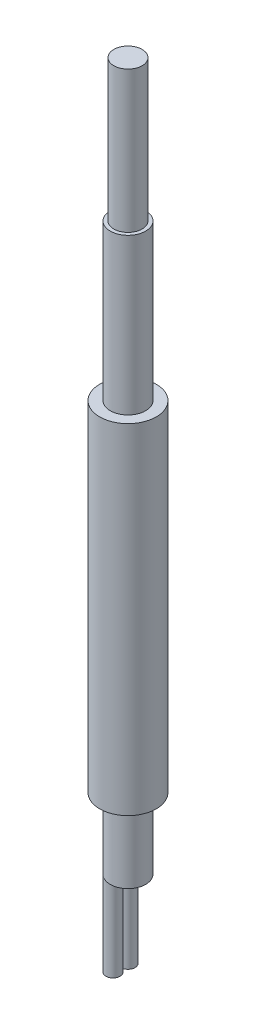
SolidWorks part; units mm, degrees
ref_plane "Ebene vorne" through (0, 0, 0) normal (0, 0, 1) x (1, 0, 0)
ref_plane "Ebene oben" through (0, 0, 0) normal (0, 1, 0) x (1, 0, 0)
ref_plane "Ebene rechts" through (0, 0, 0) normal (1, 0, 0) x (0, 0, -1)
sketch "Skizze1" plane through (0, 0, 0) normal (0, 1, 0) x (1, 0, 0)
  circle A0 centre (0, 0) radius 0.625
  circle A1 centre (0, 0) radius 0.5
  dimension "D1" = 1.25
  dimension "D2" = 0.125
extrude "Aufsatz-Linear austragen1" add sketch "Skizze1" along normal blind 20
sketch "Skizze2" plane through (0, 20, 0) normal (0, 1, 0) x (1, 0, 0)
  circle A0 centre (0, 0) radius 0.5
  dimension "D1" = 1
extrude "Aufsatz-Linear austragen2" add sketch "Skizze2" along normal blind 5 and the other way up to surface (20 mm away) separate body other way up to face at (0, 0, 0.625)
ref_plane "Ebene1" through (0, 2.5, 0) normal (0, 1, 0) x (1, 0, 0)
sketch "Skizze3" plane through (0, 2.5, 0) normal (0, 1, 0) x (1, 0, 0)
  circle A0 centre (0, 0) radius 1
  dimension "D1" = 2
extrude "Linear-Austragen-Dünn1" add sketch "Skizze3" along normal blind 12 separate body thin thin type one direction reverse wall 0.375
sketch "Skizze5" plane through (0, 0, 0) normal (0, -1, 0) x (1, 0, 0)
  line L0 (0, 0) -> (-0.625, 0) construction
  line L1 (0, 0) -> (0, -0.625) construction
  line L2 (0, 0) -> (-0.2652, -0.2652) construction
  circle A0 centre (0, 0) radius 0.625 construction
  circle A1 centre (-0.2652, -0.2652) radius 0.25
  circle A2 centre (0, 0) radius 0.625 construction
  circle A3 centre (-0.2652, 0.2652) radius 0.25
  dimension "D2" = 0.5
  dimension "D1" = 315
extrude "Aufsatz-Linear austragen3" add sketch "Skizze5" along normal blind 3
